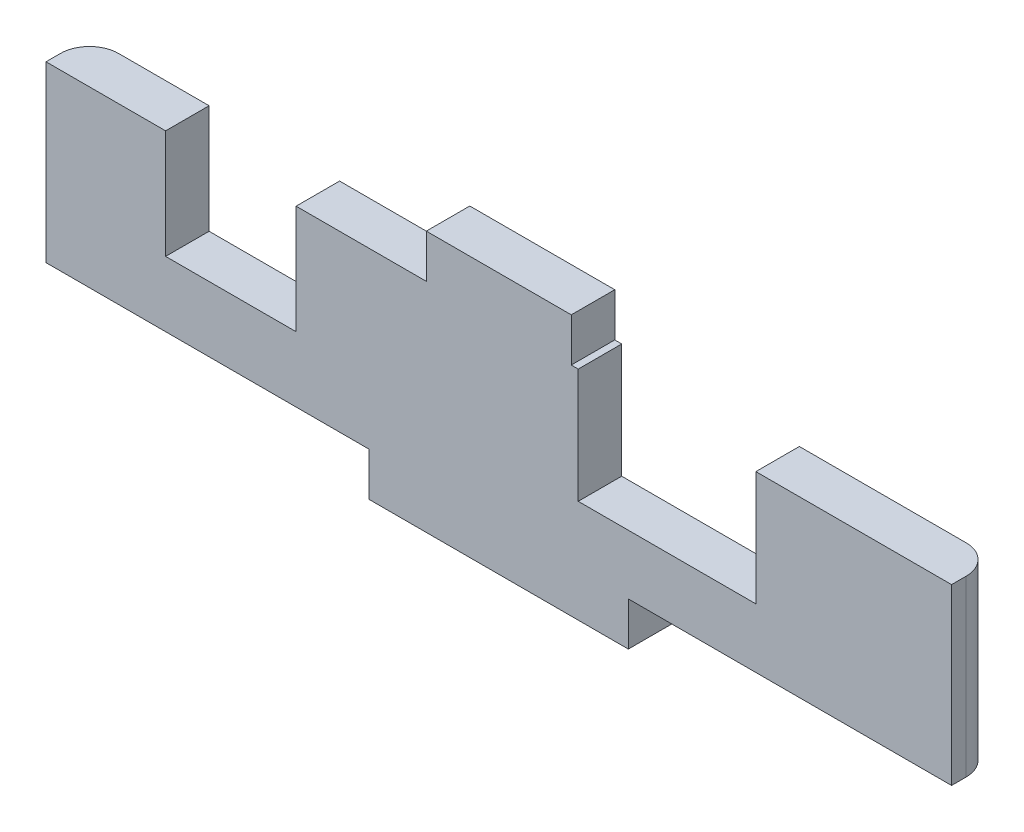
SolidWorks part; units mm, degrees
ref_plane "Front Plane" through (0, 0, 0) normal (0, 0, 1) x (1, 0, 0)
ref_plane "Top Plane" through (0, 0, 0) normal (0, 1, 0) x (1, 0, 0)
ref_plane "Right Plane" through (0, 0, 0) normal (1, 0, 0) x (0, 0, -1)
sketch "Sketch1" plane through (0, 0, 0) normal (0, 0, 1) x (1, 0, 0)
  line L0 (0, 9) -> (0, 16.0756) construction
  line L1 (-31.23, 9) -> (31.23, 9)
  line L2 (-31.23, 9) -> (-31.23, -9)
  line L3 (-31.23, -9) -> (31.23, -9)
  line L4 (31.23, 9) -> (31.23, -9)
  line L5 (-31.23, 9) -> (31.23, -9) construction
  line L6 (-31.23, -9) -> (31.23, 9) construction
  point P0 (0, 0)
  dimension "D1" = 18
  dimension "D2" = 62.46
extrude "Boss-Extrude1" add sketch "Sketch1" along normal blind 3
sketch "Sketch2" plane through (0, 0, 3) normal (0, 0, 1) x (1, 0, 0)
  line L1 (31.23, -9) -> (8.935, -9)
  line L2 (31.23, -9) -> (31.23, -6)
  line L3 (31.23, -6) -> (8.935, -6)
  line L4 (8.935, -9) -> (8.935, -6)
  line L5 (-31.23, -9) -> (-8.935, -9)
  line L6 (-31.23, -9) -> (-31.23, -6)
  line L7 (-31.23, -6) -> (-8.935, -6)
  line L8 (-8.935, -9) -> (-8.935, -6)
  dimension "D1" = 22.295
  dimension "D2" = 3
  dimension "D3" = 17.87
  dimension "D4" = 3
extrude "Cut-Extrude1" cut sketch "Sketch2" against normal blind 3
sketch "Sketch3" plane through (0, 0, 3) normal (0, 0, 1) x (1, 0, 0)
  line L0 (31.23, 9) -> (-31.23, 9) construction
  line L1 (17.73, 9) -> (5.48, 9)
  line L2 (17.73, 9) -> (17.73, -1.9)
  line L3 (17.73, -1.9) -> (5.48, -1.9)
  line L4 (5.48, 9) -> (5.48, -1.9)
  line L5 (31.23, -6) -> (31.23, 9) construction
  line L7 (-22.98, 9) -> (-13.98, 9)
  line L8 (-22.98, 9) -> (-22.98, -1.5)
  line L9 (-22.98, -1.5) -> (-13.98, -1.5)
  line L10 (-13.98, 9) -> (-13.98, -1.5)
  line L12 (-31.23, 9) -> (-31.23, -6) construction
  dimension "D1" = 10.9
  dimension "D2" = 12.25
  dimension "D3" = 13.5
  dimension "D4" = 10.5
  dimension "D5" = 9
  dimension "D6" = 8.25
extrude "Cut-Extrude2" cut sketch "Sketch3" against normal blind 3
sketch "Sketch4" plane through (0, 0, 0) normal (0, 0, -1) x (-1, 0, 0)
  line L0 (31.23, 9) -> (31.23, -6) construction
  line L1 (-5.07, 8.3746) -> (4.93, 8.3746)
  line L2 (-5.07, 8.3746) -> (-5.07, 5.3746)
  line L3 (-5.07, 5.3746) -> (4.93, 5.3746)
  line L4 (4.93, 8.3746) -> (4.93, 5.3746)
  dimension "D1" = 3
  dimension "D2" = 26.3
  dimension "D3" = 10
sketch "Sketch5" plane through (0, 0, 0) normal (0, 0, -1) x (-1, 0, 0)
  line L2 (31.23, 9) -> (5, 9)
  line L3 (31.23, 9) -> (31.23, 6)
  line L4 (31.23, 6) -> (5, 6)
  line L5 (5, 9) -> (5, 6)
  line L6 (-31.23, 9) -> (-5, 9)
  line L7 (-31.23, 9) -> (-31.23, 6)
  line L8 (-31.23, 6) -> (-5, 6)
  line L9 (-5, 9) -> (-5, 6)
  dimension "D1" = 3
  dimension "D2" = 3
  dimension "D3" = 26.23
  dimension "D4" = 26.23
extrude "Cut-Extrude3" cut sketch "Sketch5" against normal blind 3
fillet "Fillet1" radius 2 1 edges at (-31.23, 0, 0)
fillet "Fillet2" radius 2 1 edges at (31.23, 0, 0)
